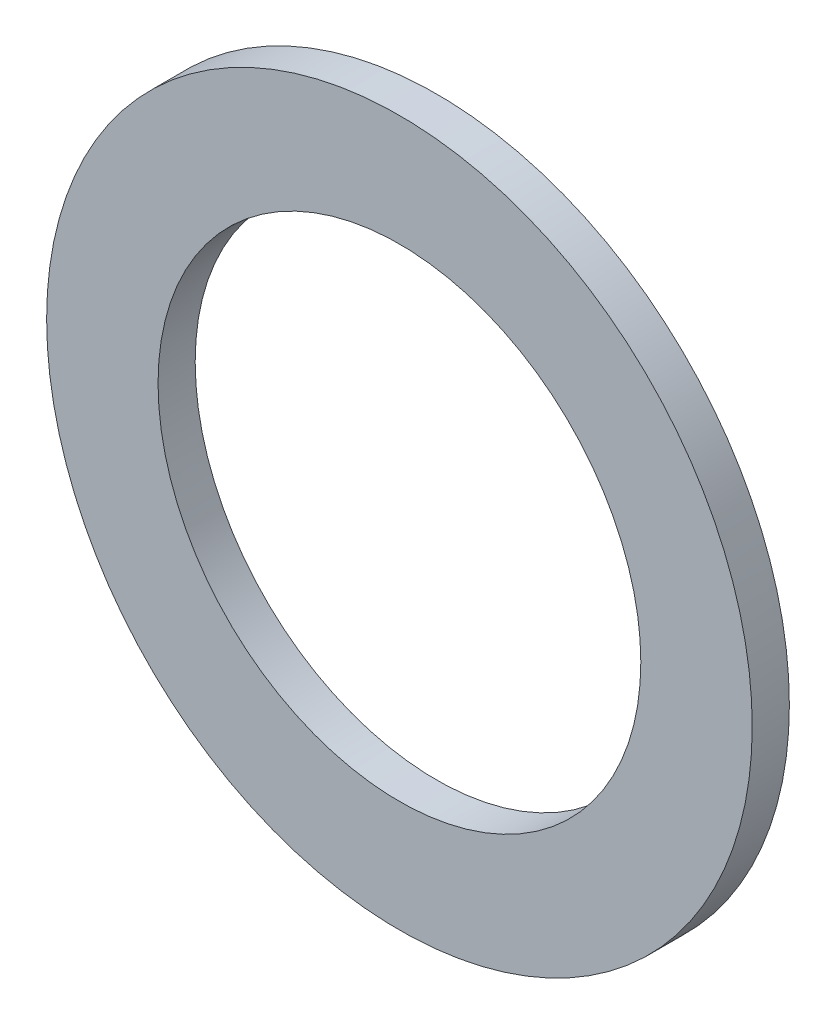
SolidWorks part; units mm, degrees
ref_plane "Front Plane" through (0, 0, 0) normal (0, 0, 1) x (1, 0, 0)
ref_plane "Top Plane" through (0, 0, 0) normal (0, 1, 0) x (1, 0, 0)
ref_plane "Right Plane" through (0, 0, 0) normal (1, 0, 0) x (0, 0, -1)
sketch "Sketch1" plane through (0, 0, 0) normal (0, 0, 1) x (1, 0, 0)
  circle A0 centre (0, 0) radius 6.5
  circle A1 centre (0, 0) radius 9.5
  dimension "D1" = 13
  dimension "D2" = 19
extrude "Boss-Extrude1" add sketch "Sketch1" along normal blind 1
